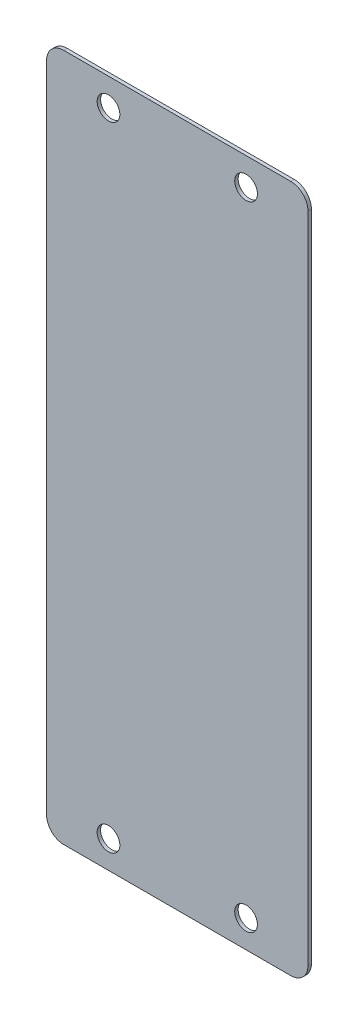
SolidWorks part; units mm, degrees
ref_plane "前视基准面" through (0, 0, 0) normal (0, 0, 1) x (1, 0, 0)
ref_plane "上视基准面" through (0, 0, 0) normal (0, 1, 0) x (1, 0, 0)
ref_plane "右视基准面" through (0, 0, 0) normal (1, 0, 0) x (0, 0, -1)
sketch "草图1" plane through (0, 0, 0) normal (0, 0, 1) x (1, 0, 0)
  line L1 (-38, 100) -> (38, 100)
  line L2 (-38, 100) -> (-38, -100)
  line L3 (-38, -100) -> (38, -100)
  line L4 (38, 100) -> (38, -100)
  line L5 (-38, 100) -> (38, -100) construction
  line L6 (-38, -100) -> (38, 100) construction
  point P0 (0, 0)
  dimension "D1" = 76
  dimension "D2" = 200
extrude "凸台-拉伸1" add sketch "草图1" along normal blind 1
sketch "草图2" plane through (0, 0, 1) normal (0, 0, 1) x (1, 0, 0)
  line L0 (38, 100) -> (-38, 100) construction
  line L1 (-20, -92) -> (20, -92) construction
  line L2 (-20, -92) -> (-20, 92) construction
  line L3 (-20, 92) -> (20, 92) construction
  line L4 (20, -92) -> (20, 92) construction
  line L5 (-20, -92) -> (20, 92) construction
  line L6 (-20, 92) -> (20, -92) construction
  circle A0 centre (-20, 92) radius 3.3
  circle A1 centre (20, 92) radius 3.3
  circle A2 centre (-20, -92) radius 3.3
  circle A3 centre (20, -92) radius 3.3
  point P0 (0, 0)
  dimension "D3" = 6.6
  dimension "D1" = 40
  dimension "D2" = 8
extrude "切除-拉伸1" cut sketch "草图2" against normal through all
fillet "圆角1" radius 5 4 edges at (-38, -100, 0.5) (38, -100, 0.5) (-38, 100, 0.5) (38, 100, 0.5)
